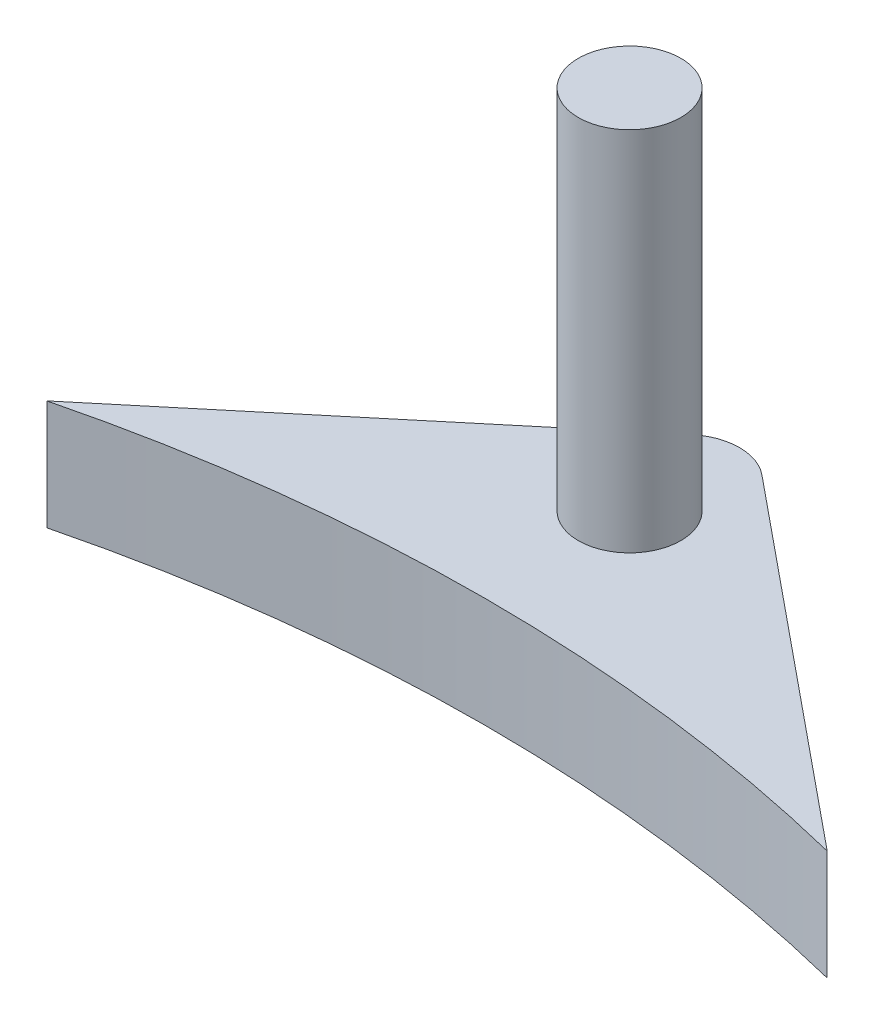
SolidWorks part; units mm, degrees
ref_plane "Front Plane" through (0, 0, 0) normal (0, 0, 1) x (1, 0, 0)
ref_plane "Top Plane" through (0, 0, 0) normal (0, 1, 0) x (1, 0, 0)
ref_plane "Right Plane" through (0, 0, 0) normal (1, 0, 0) x (0, 0, -1)
sketch "Sketch1" plane through (0, 0, 0) normal (0, 1, 0) x (1, 0, 0)
  line L0 (-0.9606, 1.1521) -> (-10.5549, -6.8479)
  line L1 (0.9496, 1.1611) -> (10.7313, -6.8389)
  arc A0 (0.9496, 1.1611) -> (-0.9606, 1.1521) centre (0, 0) ccw
  arc A1 (-10.5549, -6.8479) -> (10.7313, -6.8389) centre (0.1064, -49.4689) cw
  point P1 (0, 0)
  point P8 (0, 0)
  point P9 (0, 0)
  dimension "D1" = 3
  dimension "D2" = 8
  dimension "D3" = 8
extrude "Boss-Extrude1" add sketch "Sketch1" along normal blind 3
sketch "Sketch2" plane through (0, 3, 0) normal (0, 1, 0) x (1, 0, 0)
  circle A0 centre (0, -1.5) radius 1.4
  arc A1 (0.9496, 1.1611) -> (-0.9606, 1.1521) centre (0, 0) ccw construction
  dimension "D1" = 2.8
  dimension "D2" = 1.5
extrude "Boss-Extrude2" add sketch "Sketch2" along normal blind 10
